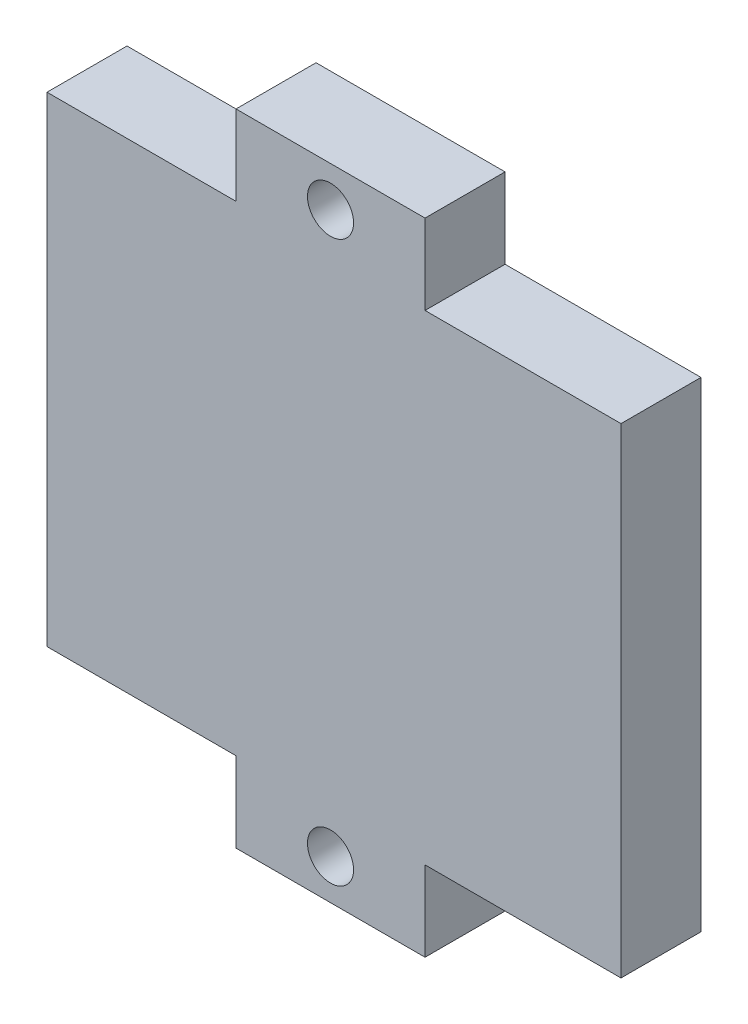
SolidWorks part; units mm, degrees
material "Beech"
ref_plane "Front Plane" through (0, 0, 0) normal (0, 0, 1) x (1, 0, 0)
ref_plane "Top Plane" through (0, 0, 0) normal (0, 1, 0) x (1, 0, 0)
ref_plane "Right Plane" through (0, 0, 0) normal (1, 0, 0) x (0, 0, -1)
sketch "Sketch1" plane through (0, 0, 0) normal (0, 0, 1) x (1, 0, 0)
  line L1 (-22.775, -25.4) -> (22.775, -25.4)
  line L2 (-22.775, -25.4) -> (-22.775, 25.4)
  line L3 (-22.775, 25.4) -> (22.775, 25.4)
  line L4 (22.775, -25.4) -> (22.775, 25.4)
  line L5 (-22.775, -25.4) -> (22.775, 25.4) construction
  line L6 (-22.775, 25.4) -> (22.775, -25.4) construction
  point P0 (0, 0)
  dimension "D1" = 50.8
  dimension "D2" = 45.55
extrude "Boss-Extrude1" add sketch "Sketch1" along normal blind 6.35
sketch "Sketch2" plane through (0, 0, 6.35) normal (0, 0, 1) x (1, 0, 0)
  line L2 (-22.775, -25.4) -> (-7.775, -25.4)
  line L3 (-22.775, -25.4) -> (-22.775, -19.05)
  line L4 (-22.775, -19.05) -> (-7.775, -19.05)
  line L6 (-7.775, -25.4) -> (-7.775, -19.05)
  line L7 (22.775, -25.4) -> (7.225, -25.4)
  line L8 (22.775, -25.4) -> (22.775, -19.05)
  line L9 (22.775, -19.05) -> (7.225, -19.05)
  line L10 (7.225, -25.4) -> (7.225, -19.05)
  dimension "D1" = 6.35
  dimension "D2" = 15
  dimension "D3" = 15
extrude "Cut-Extrude1" cut sketch "Sketch2" against normal blind 6.35
hole_wizard "#6 Clearance Hole1" positions "Sketch3" profile "Sketch4" hole size "#6" standard "ANSI Inch" end condition up to next
sketch "Sketch3" plane through (0, 0, 6.35) normal (0, 0, 1) x (1, 0, 0)
  line L1 (-7.775, -22.225) -> (7.225, -22.225) construction
  line L2 (-7.775, -25.4) -> (-7.775, -19.05) construction
  line L3 (7.225, -19.05) -> (7.225, -25.4) construction
  point P11 (-0.275, -22.225)
sketch "Sketch4" plane through (-0.275, -22.225, 6.35) normal (1, 0, 0) x (0, -1, 0)
  line L0 (0, 0) -> (0, 6.351)
  line L1 (0, 6.351) -> (1.8288, 6.351)
  line L2 (1.8288, 6.351) -> (1.8288, 0)
  line L5 (1.8288, 0) -> (0, 0)
  line L11 (0, -6.35) -> (0, 107.95) construction
  dimension "Thru Hole Dia." = 3.6576
  dimension "Thru Hole Depth" = 6.351
mirror "Mirror1" about plane through (0, 0, 0) normal (0, 1, 0) of "#6 Clearance Hole1", "Cut-Extrude1"
